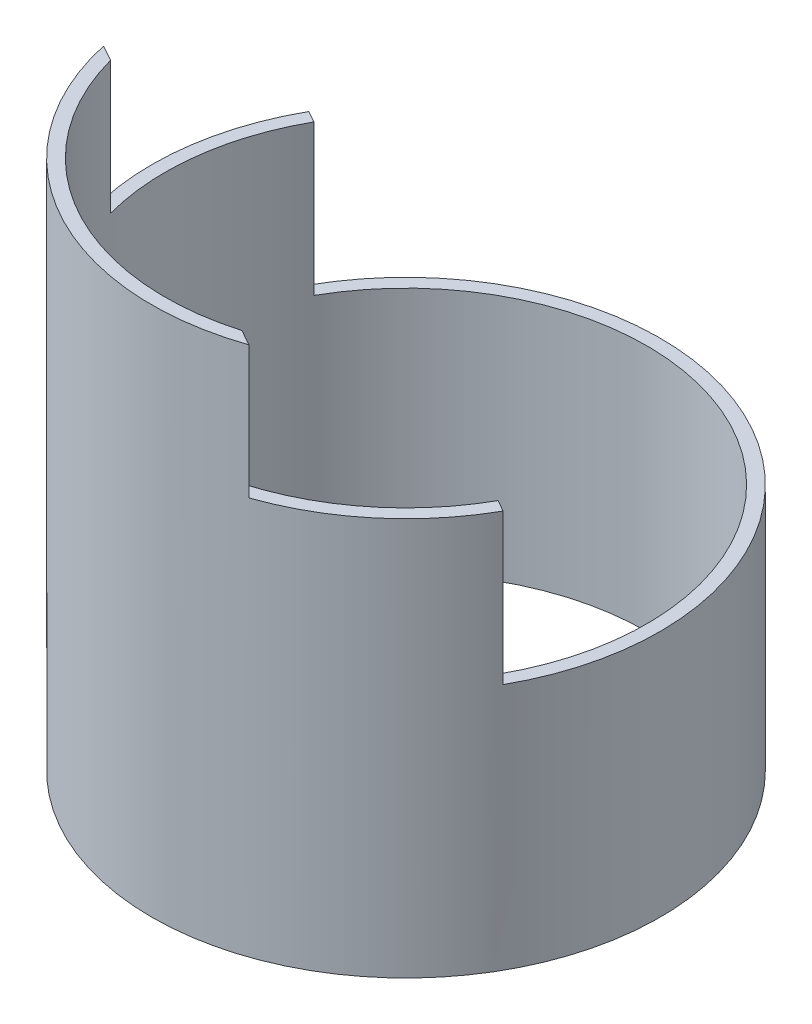
SolidWorks part; units mm, degrees
ref_plane "Front Plane" through (0, 0, 0) normal (0, 0, 1) x (1, 0, 0)
ref_plane "Top Plane" through (0, 0, 0) normal (0, 1, 0) x (1, 0, 0)
ref_plane "Right Plane" through (0, 0, 0) normal (1, 0, 0) x (0, 0, -1)
sketch "Sketch1" plane through (0, 0, 0) normal (0, 1, 0) x (1, 0, 0)
  circle A0 centre (0, 0) radius 54.5
  circle A1 centre (0, 0) radius 57.5
  dimension "D1" = 109
  dimension "D2" = 3
extrude "Boss-Extrude1" add sketch "Sketch1" along normal blind 120
sketch "Sketch2" plane through (-168.9329, 99.4365, -468.1144) normal (0, 0, 1) x (1, 0, 0)
  line L0 (111.4329, 20.5635) -> (111.4329, -99.4365) construction
  line L1 (111.4329, 150.5635) -> (226.4329, 150.5635) construction
  line L2 (111.4329, 150.5635) -> (111.4329, 50.5635) construction
  line L3 (111.4329, 50.5635) -> (226.4329, 50.5635) construction
  line L4 (226.4329, 150.5635) -> (226.4329, 50.5635) construction
  line L5 (226.4329, -99.4365) -> (226.4329, 20.5635) construction
  line L6 (118.4329, 143.5635) -> (118.4329, 57.5635)
  line L7 (118.4329, 57.5635) -> (219.4329, 57.5635)
  line L8 (219.4329, 143.5635) -> (219.4329, 57.5635)
  line L9 (118.4329, 143.5635) -> (219.4329, 143.5635)
  line L10 (111.4329, -99.4365) -> (226.4329, -99.4365) construction
  dimension "D2" = 250
  dimension "D3" = 100
  dimension "D1" = 7
sketch "Sketch4" plane through (0, 120, 0) normal (0, 1, 0) x (1, 0, 0)
  line L0 (0, 0) -> (50.133, -28.159) construction
  line L1 (50.133, -28.159) -> (-50.133, 28.159) construction
  line L2 (-50.133, 28.159) -> (50.133, -28.159)
  circle A0 centre (0, 0) radius 57.5 construction
  arc A1 (-50.133, 28.159) -> (50.133, -28.159) centre (0, 0) ccw
extrude "Cut-Extrude1" cut sketch "Sketch4" against normal blind 64 flip side to cut
sketch "Sketch5" plane through (0, 120, 0) normal (0, 1, 0) x (1, 0, 0)
  line L0 (-18.7962, 54.3411) -> (56.1854, 12.225) construction
  line L1 (-50.133, 28.159) -> (50.133, -28.159) construction
  line L2 (-50.133, 28.159) -> (32.8987, -18.4787) construction
  line L3 (-56.1854, -12.225) -> (18.7962, -54.3411)
  arc A0 (50.133, -28.159) -> (-50.133, 28.159) centre (0, 0) ccw construction
  arc A1 (-18.7962, 54.3411) -> (56.1854, 12.225) centre (0, 0) cw construction
  arc A2 (-56.1854, -12.225) -> (18.7962, -54.3411) centre (0, 0) ccw
  dimension "D1" = 86
extrude "Cut-Extrude2" cut sketch "Sketch5" against normal blind 30 flip side to cut
